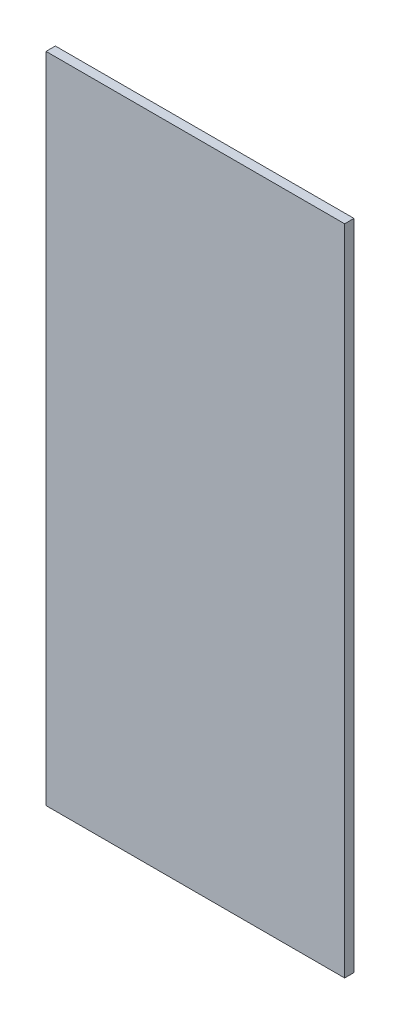
SolidWorks part; units mm, degrees
ref_plane "Alzado" through (0, 0, 0) normal (0, 0, 1) x (1, 0, 0)
ref_plane "Planta" through (0, 0, 0) normal (0, 1, 0) x (1, 0, 0)
ref_plane "Vista lateral" through (0, 0, 0) normal (1, 0, 0) x (0, 0, -1)
sketch "Croquis1" plane through (0, 0, 0) normal (0, 0, 1) x (1, 0, 0)
  line L1 (0, 0) -> (320, 0)
  line L2 (0, 0) -> (0, 700)
  line L3 (0, 700) -> (320, 700)
  line L4 (320, 0) -> (320, 700)
extrude "Saliente-Extruir1" add sketch "Croquis1" along normal blind 10
